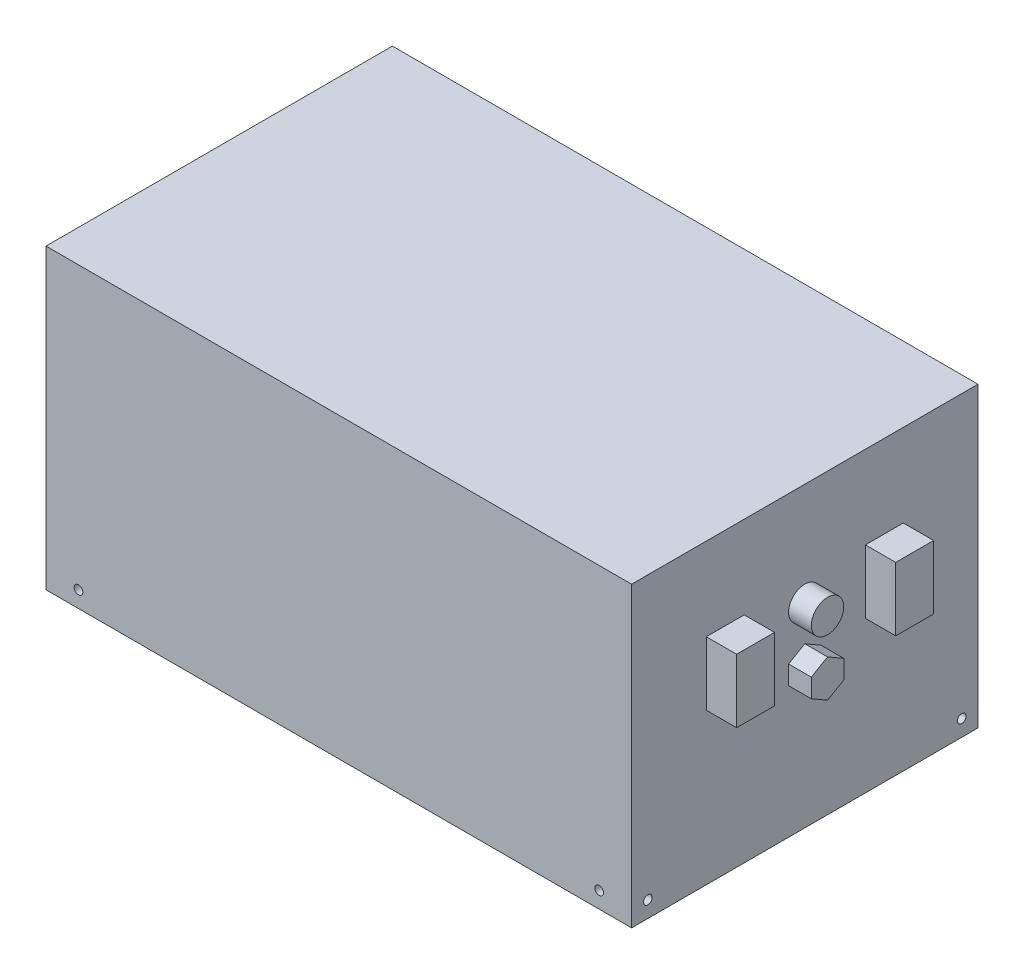
SolidWorks part; units mm, degrees
material "Lega 1060"
ref_plane "Frontale" through (0, 0, 0) normal (0, 0, 1) x (1, 0, 0)
ref_plane "Superiore" through (0, 0, 0) normal (0, 1, 0) x (1, 0, 0)
ref_plane "Destro" through (0, 0, 0) normal (1, 0, 0) x (0, 0, -1)
other "Centro di massa"
sketch "Schizzo1" plane through (0, 0, 0) normal (0, 1, 0) x (1, 0, 0)
  line L1 (-270.5, -160) -> (270.5, -160)
  line L2 (-270.5, -160) -> (-270.5, 160)
  line L3 (-270.5, 160) -> (270.5, 160)
  line L4 (270.5, -160) -> (270.5, 160)
  line L5 (-270.5, -160) -> (270.5, 160) construction
  line L6 (-270.5, 160) -> (270.5, -160) construction
  point P0 (0, 0)
  dimension "D1" = 541
  dimension "D2" = 320
extrude "Estrusione-Estrusione1" add sketch "Schizzo1" along normal blind 275
sketch "Schizzo2" plane through (270.5, 0, 0) normal (1, 0, 0) x (0, 0, -1)
  line L1 (-91, 198.45) -> (-56, 198.45)
  line L2 (-91, 198.45) -> (-91, 139.65)
  line L3 (-91, 139.65) -> (-56, 139.65)
  line L4 (-56, 198.45) -> (-56, 139.65)
  line L5 (-91, 198.45) -> (-56, 139.65) construction
  line L6 (-91, 139.65) -> (-56, 198.45) construction
  line L7 (56, 198.45) -> (91, 198.45)
  line L8 (56, 198.45) -> (56, 139.65)
  line L9 (56, 139.65) -> (91, 139.65)
  line L10 (91, 198.45) -> (91, 139.65)
  line L11 (56, 198.45) -> (91, 139.65) construction
  line L12 (56, 139.65) -> (91, 198.45) construction
  line L13 (0, 0) -> (0, 275) construction
  line L14 (-160, 275) -> (160, 275) construction
  line L16 (-160, 0) -> (160, 0) construction
  point P0 (-73.5, 169.05)
  point P5 (73.5, 169.05)
  dimension "D1" = 198.45
  dimension "D2" = 147
  dimension "D3" = 35
  dimension "D4" = 58.8
extrude "Estrusione-Estrusione2" add sketch "Schizzo2" along normal blind 28
sketch "Schizzo3" plane through (270.5, 0, 0) normal (1, 0, 0) x (0, 0, -1)
  line L0 (0, 0) -> (0, 275) construction
  line L1 (-160, 0) -> (160, 0) construction
  line L3 (0, 147.3205) -> (-15, 138.6603)
  line L4 (-15, 138.6603) -> (-15, 121.3397)
  line L5 (-15, 121.3397) -> (0, 112.6795)
  line L6 (0, 112.6795) -> (15, 121.3397)
  line L7 (15, 121.3397) -> (15, 138.6603)
  line L8 (15, 138.6603) -> (0, 147.3205)
  circle A0 centre (0, 180) radius 15
  circle A1 centre (0, 130) radius 15 construction
  dimension "D1" = 180
  dimension "D4" = 30
  dimension "D2" = 30
  dimension "D3" = 50
extrude "Estrusione-Estrusione3" add sketch "Schizzo3" along normal blind 21
sketch "Schizzo4" plane through (270.5, 0, 0) normal (1, 0, 0) x (0, 0, -1)
  line L0 (-160, 275) -> (-160, 0) construction
  line L2 (-160, 0) -> (160, 0) construction
  circle A0 centre (-145, 15) radius 4
  circle A1 centre (145, 15) radius 4
  dimension "D1" = 15
  dimension "D2" = 290
  dimension "D3" = 15
  dimension "D4" = 8
extrude "Taglio-Estrusione1" cut sketch "Schizzo4" against normal blind 15
mirror "Specchia1" about plane through (0, 0, 0) normal (1, 0, 0) of "Taglio-Estrusione1"
sketch "Schizzo5" plane through (0, 0, 160) normal (0, 0, 1) x (1, 0, 0)
  line L0 (-270.5, 275) -> (-270.5, 0) construction
  line L1 (270.5, 0) -> (270.5, 275) construction
  line L2 (-270.5, 0) -> (270.5, 0) construction
  circle A0 centre (-240.5, 15) radius 4
  circle A1 centre (240.5, 15) radius 4
  dimension "D1" = 30
  dimension "D2" = 30
  dimension "D3" = 15
  dimension "D4" = 8
extrude "Taglio-Estrusione2" cut sketch "Schizzo5" against normal blind 15
other "Punto di riferimento centro di massa1"
